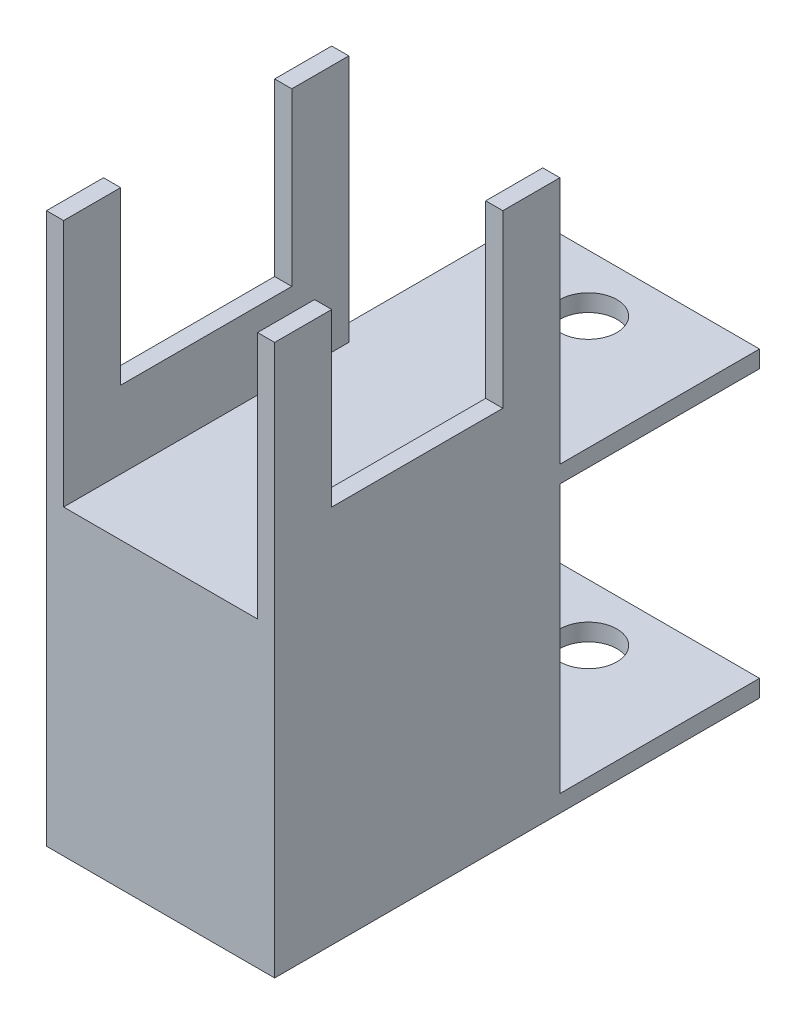
SolidWorks part; units mm, degrees
material "Baustahl Künz"
ref_plane "Ebene vorne" through (0, 0, 0) normal (0, 0, 1) x (1, 0, 0)
ref_plane "Ebene oben" through (0, 0, 0) normal (0, 1, 0) x (1, 0, 0)
ref_plane "Ebene rechts" through (0, 0, 0) normal (1, 0, 0) x (0, 0, -1)
sketch "Skizze1" plane through (0, 0, 0) normal (1, 0, 0) x (0, 0, -1)
  line L0 (0, 23.5) -> (0, -23.5) construction
  line L1 (-25, 23.5) -> (10, 23.5)
  line L2 (10, 23.5) -> (10, 26.5)
  line L3 (10, 26.5) -> (-25, 26.5)
  line L4 (-25, 23.5) -> (-25, -23.5)
  line L5 (-25, -23.5) -> (10, -23.5)
  line L6 (10, -23.5) -> (10, -26.5)
  line L7 (10, -26.5) -> (-75, -26.5)
  line L8 (-75, -26.5) -> (-75, 70)
  line L9 (-75, 70) -> (-65, 70)
  line L10 (-65, 70) -> (-65, 40)
  line L11 (-65, 40) -> (-35, 40)
  line L12 (-35, 40) -> (-35, 70)
  line L13 (-35, 70) -> (-25, 70)
  line L14 (-25, 70) -> (-25, 26.5)
  point P5 (-20, 72.0821)
  dimension "D1" = 47
  dimension "D2" = 3
  dimension "D3" = 10
  dimension "D4" = 25
  dimension "D5" = 30
  dimension "D6" = 30
  dimension "D7" = 50
  dimension "D8" = 40
extrude "Aufsatz-Linear austragen1" add sketch "Skizze1" along normal mid plane 40
sketch "Skizze2" plane through (0, 0, 0) normal (0, 0, 1) x (1, 0, 0)
  line L0 (20, 70) -> (-20, 70) construction
  line L1 (17, 70) -> (-17, 70)
  line L2 (17, 70) -> (17, 26.5)
  line L3 (17, 26.5) -> (-17, 26.5)
  line L4 (-17, 70) -> (-17, 26.5)
  line L5 (20, 26.5) -> (20, 70) construction
  line L6 (0, 0) -> (0, 26.5) construction
  line L7 (20, 26.5) -> (-20, 26.5) construction
  point P11 (-12, 26.5)
  dimension "D1" = 3
extrude "Schnitt-Linear austragen1" cut sketch "Skizze2" along normal through all
sketch "Skizze3" plane through (0, 0, 0) normal (0, 1, 0) x (1, 0, 0)
  circle A0 centre (0, 0) radius 5
  dimension "D1" = 10
extrude "Schnitt-Linear austragen2" cut sketch "Skizze3" against normal through all both and the other way through all
